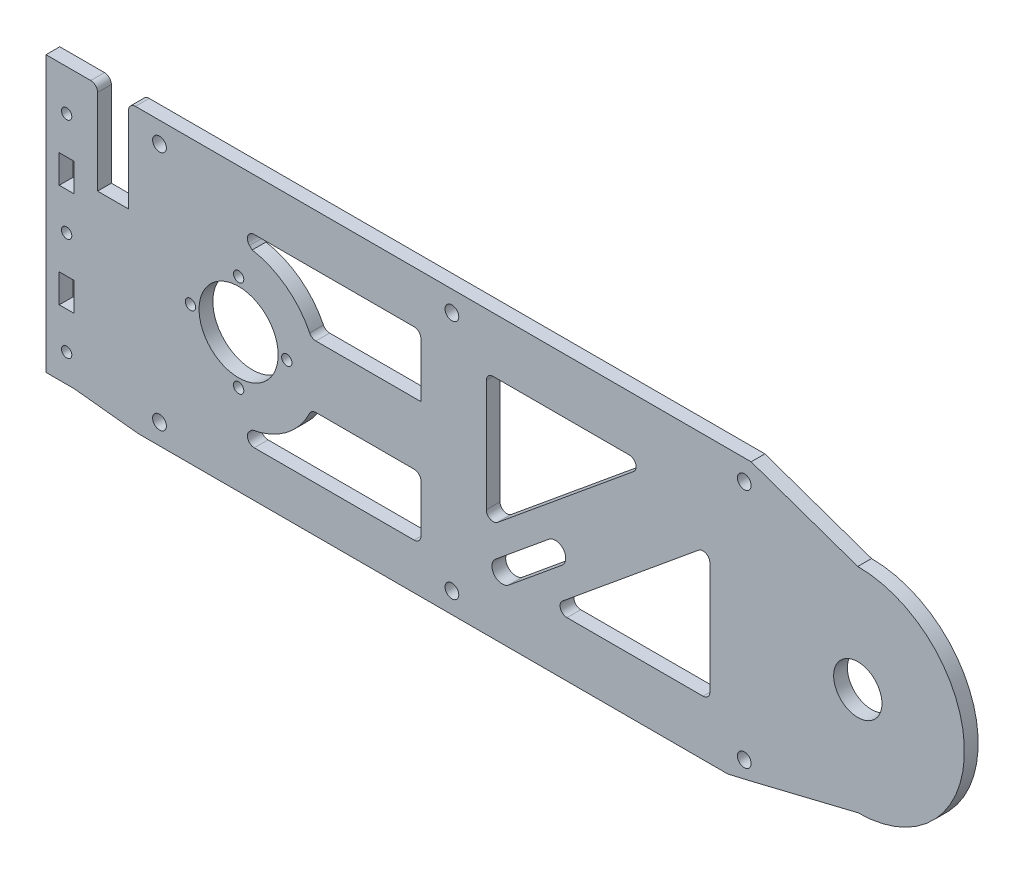
SolidWorks part; units mm, degrees
ref_plane "前视基准面" through (0, 0, 0) normal (0, 0, 1) x (1, 0, 0)
ref_plane "上视基准面" through (0, 0, 0) normal (0, 1, 0) x (1, 0, 0)
ref_plane "右视基准面" through (0, 0, 0) normal (1, 0, 0) x (0, 0, -1)
sketch "草图1" plane through (0, 0, 0) normal (0, 0, 1) x (1, 0, 0)
  line L0 (0.5429, 31.4043) -> (0.5429, 28.4043)
  line L1 (0.5429, 18.9043) -> (0.5429, 10.9043) construction
  line L2 (-1.6071, 10.8043) -> (2.6929, 10.8043)
  line L3 (-1.6071, 10.8043) -> (-1.6071, 19.0043)
  line L4 (-1.6071, 19.0043) -> (2.6929, 19.0043)
  line L5 (2.6929, 10.8043) -> (2.6929, 19.0043)
  line L6 (-1.6071, 10.8043) -> (2.6929, 19.0043) construction
  line L7 (-1.6071, 19.0043) -> (2.6929, 10.8043) construction
  line L8 (2.6929, -19.2957) -> (2.6929, -10.9957)
  line L9 (-1.6071, -19.2957) -> (2.6929, -19.2957)
  line L10 (-1.6071, -19.2957) -> (-1.6071, -10.9957)
  line L11 (-1.6071, -10.9957) -> (2.6929, -10.9957)
  line L12 (0.5429, -0.0957) -> (-5.4571, -0.0957) construction
  line L13 (-5.4571, -0.0957) -> (-5.4571, 41.7543)
  line L14 (-5.4571, 41.7543) -> (261.5429, 41.7543) construction
  line L15 (261.5429, 41.7543) -> (261.5429, -38.2457) construction
  line L17 (-5.4571, -38.2457) -> (-5.4571, -0.0957)
  line L18 (50.5429, -0.0957) -> (96.7433, -0.0957) construction
  line L19 (50.5429, -0.0957) -> (230.5429, -0.0957) construction
  line L21 (199.5429, -0.0957) -> (199.5429, 41.7543) construction
  line L23 (199.5429, 41.7543) -> (230.5429, 30.9043)
  line L26 (230.5429, -31.0957) -> (199.5561, -38.6559)
  line L28 (-5.4571, 41.7543) -> (9.5429, 41.7543)
  line L29 (0.5429, -0.0957) -> (36.5429, -0.0957) construction
  line L32 (21.3658, -40.2457) -> (192.7469, -40.2457)
  line L38 (-5.4571, -38.2457) -> (2.6929, -38.2457)
  line L42 (18.5429, 14.9043) -> (18.5429, 41.7543)
  line L43 (18.5429, 41.7543) -> (199.5429, 41.7543)
  line L44 (9.5429, 41.7543) -> (9.5429, 14.9043)
  line L45 (9.5429, 14.9043) -> (18.5429, 14.9043)
  line L46 (2.6929, -38.2457) -> (21.3658, -40.2457)
  line L47 (192.7469, -40.2457) -> (199.5561, -38.6559)
  circle A0 centre (0.5429, 29.9043) radius 1.5
  circle A1 centre (0.5429, -0.0957) radius 1.5
  circle A2 centre (0.5429, -30.0957) radius 1.5
  circle A3 centre (50.5429, -0.0957) radius 11.5
  circle A4 centre (50.5429, -0.0957) radius 14 construction
  circle A5 centre (50.5429, -14.0957) radius 1.5
  circle A12 centre (36.5429, -0.0957) radius 1.5
  circle A13 centre (50.5429, 13.9043) radius 1.5
  circle A14 centre (64.5429, -0.0957) radius 1.5
  circle A15 centre (230.5429, -0.0957) radius 7.02
  circle A16 centre (230.5429, -0.0957) radius 31 construction
  arc A17 (230.5429, 30.9043) -> (230.5429, -31.0957) centre (230.5429, -0.0957) cw
  point P6 (0.5429, 14.9043)
  dimension "D3" = 23
  dimension "D4" = 4
  dimension "D10" = 38.15
  dimension "D13" = 14.04
  dimension "D1" = 8.2
  dimension "D2" = 4.3
  dimension "D5" = 50
  dimension "D6" = 6
  dimension "D7" = 15
  dimension "D8" = 60
  dimension "D9" = 30
  dimension "D11" = 41.85
  dimension "D12" = 31
  dimension "D14" = 180
  dimension "D15" = 2
  dimension "D17" = 15
extrude "凸台-拉伸1" add sketch "草图1" along normal blind 4
sketch "草图2" plane through (0, 0, 4) normal (0, 0, 1) x (1, 0, 0)
  line L0 (112.5429, -34.2457) -> (197.5429, 35.7543) construction
  line L1 (197.5429, 35.7543) -> (197.5429, -34.2457) construction
  line L2 (197.5429, -34.2457) -> (112.5429, -34.2457) construction
  line L3 (187.5429, -24.2457) -> (140.4162, -24.2457)
  line L4 (140.4162, -24.2457) -> (187.5429, 14.5645)
  line L5 (187.5429, 14.5645) -> (187.5429, -24.2457)
  line L6 (112.5429, -34.2457) -> (112.5429, 35.7543) construction
  line L7 (112.5429, 35.7543) -> (197.5429, 35.7543) construction
  line L8 (122.5429, 25.7543) -> (169.6695, 25.7543)
  line L9 (122.5429, -13.0559) -> (169.6695, 25.7543)
  line L10 (122.5429, -13.0559) -> (122.5429, 25.7543)
  line L11 (27.5429, 35.7543) -> (50.5429, 13.9043) construction
  line L13 (64.5429, -0.0957) -> (112.5429, -0.0957) construction
  line L18 (18.5429, 41.7543) -> (199.5429, 41.7543) construction
  line L19 (18.5429, 14.9043) -> (18.5429, 41.7543) construction
  line L20 (127.1861, -22.1866) -> (142.6247, -9.4724) construction
  line L23 (27.5429, 35.7543) -> (112.5429, 35.7543) construction
  line L24 (112.5429, -0.0957) -> (112.5429, 35.7543) construction
  line L25 (71.7089, 8.9043) -> (103.5429, 8.9043)
  line L26 (103.5429, 8.9043) -> (103.5429, 26.7543)
  line L27 (50.0837, 26.7543) -> (103.5429, 26.7543)
  line L28 (50.0837, 26.7543) -> (54.4968, 22.5619)
  line L29 (103.5429, -9.0957) -> (103.5429, -26.9457)
  line L30 (71.7089, -9.0957) -> (103.5429, -9.0957)
  line L31 (50.0837, -26.9457) -> (54.4968, -22.7533)
  line L32 (50.0837, -26.9457) -> (103.5429, -26.9457)
  line L38 (125.279, -19.8708) -> (140.7176, -7.1566)
  line L39 (129.0932, -24.5023) -> (144.5319, -11.7882)
  line L40 (112.5429, -34.2457) -> (27.5429, -34.2457) construction
  circle A0 centre (27.5429, 35.7543) radius 2
  circle A1 centre (112.5429, 35.7543) radius 2
  circle A2 centre (197.5429, 35.7543) radius 2
  circle A3 centre (112.5429, -34.2457) radius 2
  circle A4 centre (197.5429, -34.2457) radius 2
  circle A5 centre (27.5429, -34.2457) radius 2
  arc A8 (50.5429, 13.9043) -> (64.5429, -0.0957) centre (50.5429, -0.0957) cw construction
  arc A9 (54.4968, 22.5619) -> (71.7089, 8.9043) centre (50.5429, -0.0957) cw
  arc A10 (54.4968, -22.7533) -> (71.7089, -9.0957) centre (50.5429, -0.0957) ccw
  arc A11 (125.279, -19.8708) -> (129.0932, -24.5023) centre (127.1861, -22.1866) ccw
  arc A12 (144.5319, -11.7882) -> (140.7176, -7.1566) centre (142.6247, -9.4724) ccw
  point P24 (27.5429, 35.7543)
  point P31 (134.9054, -15.8295)
  dimension "D3" = 9
  dimension "D4" = 9
  dimension "D1" = 6
  dimension "D2" = 9
  dimension "D5" = 85
  dimension "D6" = 85
  dimension "D7" = 70
extrude "切除-拉伸1" cut sketch "草图2" against normal blind 4
fillet "圆角1" radius 2 15 edges at (187.5429, -24.2457, 2) (140.4162, -24.2457, 2) (187.5429, 14.5645, 2) (169.6695, 25.7543, 2) (122.5429, -13.0559, 2) (122.5429, 25.7543, 2) (71.7089, 8.9043, 2) (71.7089, -9.0957, 2) (50.0837, -26.9457, 2) (103.5429, -26.9457, 2) (50.0837, 26.7543, 2) (103.5429, 26.7543, 2) (103.5429, -9.0957, 2) (18.5429, 41.7543, 2) (9.5429, 41.7543, 2)
